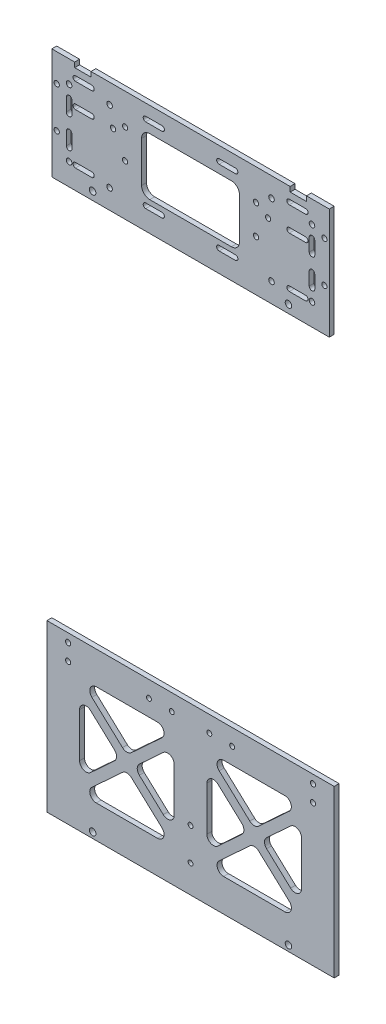
SolidWorks part; units mm, degrees
material "Thornel Mat VMA"
ref_plane "前视基准面" through (0, 0, 0) normal (0, 0, 1) x (1, 0, 0)
ref_plane "上视基准面" through (0, 0, 0) normal (0, 1, 0) x (1, 0, 0)
ref_plane "右视基准面" through (0, 0, 0) normal (1, 0, 0) x (0, 0, -1)
sketch "草图1" plane through (0, 0, 0) normal (0, 0, 1) x (1, 0, 0)
  line L0 (0, 211.445) -> (0, -244.9446) construction
  line L1 (-167.2368, 0) -> (136.1482, 0) construction
  line L3 (-88, -173.5) -> (88, -173.5)
  line L4 (-88, -173.5) -> (-88, 230)
  line L5 (-88, 230) -> (88, 230)
  line L6 (88, -173.5) -> (88, 230)
  line L7 (-88, -173.5) -> (88, 230) construction
  line L8 (-88, 230) -> (88, -173.5) construction
  circle A0 centre (-60, 170) radius 2
  circle A1 centre (60, 170) radius 2
  circle A2 centre (-60, -170) radius 2
  circle A3 centre (60, -170) radius 2
  point P14 (0, 28.25)
  dimension "D1" = 4
  dimension "D2" = 120
  dimension "D3" = 340
  dimension "D4" = 176
  dimension "D5" = 3.5
  dimension "D6" = 60
extrude "凸台-拉伸1" add sketch "草图1" along normal blind 3
sketch "草图3" plane through (0, 0, 0) normal (0, 0, -1) x (-1, 0, 0)
  line L0 (0, 280) -> (0, -209.7777) construction
  line L1 (-88, 230) -> (88, 230) construction
  line L2 (88, -173.5) -> (-88, -173.5) construction
  line L3 (-30, 218) -> (30, 218)
  line L4 (-30, 218) -> (-30, 183)
  line L5 (-30, 183) -> (30, 183)
  line L6 (30, 218) -> (30, 183)
  line L7 (-30, 218) -> (30, 183) construction
  line L8 (-30, 183) -> (30, 218) construction
  circle A0 centre (-40.1, 214) radius 1.6
  circle A1 centre (-40.1, 196) radius 1.6
  circle A2 centre (40.1, 214) radius 1.6
  circle A3 centre (40.1, 196) radius 1.6
  circle A4 centre (0, -136.5) radius 1.5
  circle A5 centre (0, -156.5) radius 1.5
  point P5 (0, 200.5)
  dimension "D4" = 80.2
  dimension "D5" = 18
  dimension "D6" = 3.2
  dimension "D7" = 16
  dimension "D8" = 3
  dimension "D9" = 20
  dimension "D10" = 17
  dimension "D1" = 60
  dimension "D2" = 12
  dimension "D3" = 35
extrude "切除-拉伸2" cut sketch "草图3" against normal through all
sketch "草图5" plane through (0, 0, 0) normal (0, 0, -1) x (-1, 0, 0)
  line L0 (88, -173.5) -> (-88, -173.5) construction
  line L1 (0, -173.5) -> (0, -19.6064) construction
  circle A0 centre (11.5, -81.85) radius 1.5
  circle A1 centre (25.5, -81.85) radius 1.5
  circle A2 centre (0, -136.5) radius 1.5 construction
  circle A3 centre (-25.5, -81.85) radius 1.5
  circle A4 centre (-11.5, -81.85) radius 1.5
  dimension "D1" = 3
  dimension "D2" = 14
  dimension "D3" = 11.5
  dimension "D4" = 91.65
extrude "切除-拉伸3" cut sketch "草图5" against normal through all
sketch "草图7" plane through (0, 0, 0) normal (0, 0, -1) x (-1, 0, 0)
  line L0 (0, 280) -> (0, -173.5) construction
  line L2 (88, -173.5) -> (-88, -173.5) construction
  line L3 (88, 230) -> (88, -173.5) construction
  line L4 (-68, 150) -> (68, 150) construction
  line L5 (-68, 150) -> (-68, -71.85) construction
  line L6 (-68, -71.85) -> (68, -71.85) construction
  line L7 (68, 150) -> (68, -71.85) construction
  line L8 (-68, 150) -> (68, -71.85) construction
  line L9 (-68, -71.85) -> (68, 150) construction
  line L11 (-68, -91.85) -> (-10, -91.85)
  line L12 (-68, -91.85) -> (-68, -153.5)
  line L13 (-68, -153.5) -> (-10, -153.5)
  line L14 (-10, -91.85) -> (-10, -153.5)
  line L15 (-68, -91.85) -> (-10, -153.5) construction
  line L16 (-68, -153.5) -> (-10, -91.85) construction
  line L17 (10, -91.85) -> (68, -91.85)
  line L18 (10, -91.85) -> (10, -153.5)
  line L19 (10, -153.5) -> (68, -153.5)
  line L20 (68, -91.85) -> (68, -153.5)
  line L21 (10, -91.85) -> (68, -153.5) construction
  line L22 (10, -153.5) -> (68, -91.85) construction
  circle A0 centre (25.5, -81.85) radius 1.5 construction
  circle A1 centre (60, 170) radius 2 construction
  circle A2 centre (25.5, -81.85) radius 1.5 construction
  point P6 (0, 39.075)
  point P17 (-39, -122.675)
  point P22 (39, -122.675)
  dimension "D1" = 10
  dimension "D2" = 20
  dimension "D3" = 20
  dimension "D4" = 20
  dimension "D5" = 20
  dimension "D6" = 10
  dimension "D7" = 20
extrude "切除-拉伸4" cut sketch "草图7" against normal through all
sketch "草图10" [suppressed] plane through (0, 0, 0) normal (0, 0, -1) x (-1, 0, 0)
  line L1 (80, 105) -> (-80, 105)
  line L2 (80, 105) -> (80, 160)
  line L3 (80, 160) -> (-80, 160)
  line L4 (-80, 105) -> (-80, 160)
  line L5 (80, 105) -> (-80, 160) construction
  line L6 (80, 160) -> (-80, 105) construction
  line L7 (0, 132.5) -> (0, 0) construction
  line L8 (-30, 185) -> (30, 185) construction
  point P0 (0, 132.5)
  dimension "D1" = 160
  dimension "D2" = 55
  dimension "D3" = 25
extrude "切除-拉伸6" [suppressed] cut sketch "草图10" against normal through all
sketch "草图11" plane through (0, 0, 0) normal (0, 0, -1) x (-1, 0, 0)
  line L0 (0, 230) -> (0, -173.5) construction
  line L1 (-88, 230) -> (88, 230) construction
  line L2 (88, -173.5) -> (-88, -173.5) construction
  line L3 (-204.8882, 0) -> (174.296, 0) construction
  line L4 (-88, -173.5) -> (-88, 230) construction
  line L5 (-88, 165) -> (88, 165)
  line L6 (-88, 165) -> (-88, -71.85)
  line L7 (-88, -71.85) -> (88, -71.85)
  line L8 (88, 165) -> (88, -71.85)
  line L9 (88, 230) -> (88, -173.5) construction
  circle A0 centre (25.5, -81.85) radius 1.5 construction
  circle A1 centre (60, 170) radius 2 construction
  circle A2 centre (-75, -77) radius 1.6
  circle A3 centre (-75, -87) radius 1.6
  circle A4 centre (75, -77) radius 1.6
  circle A5 centre (75, -87) radius 1.6
  circle A6 centre (-82, 216) radius 1.6
  circle A7 centre (-82, 191) radius 1.6
  circle A8 centre (82, 216) radius 1.6
  circle A9 centre (82, 191) radius 1.6
  dimension "D3" = 10
  dimension "D4" = 3.2
  dimension "D5" = 13
  dimension "D6" = 86.5
  dimension "D7" = 25
  dimension "D8" = 14
  dimension "D9" = 6
  dimension "D1" = 10
  dimension "D2" = 5
extrude "切除-拉伸7" cut sketch "草图11" against normal blind 10
sketch "草图12" plane through (0, 0, 0) normal (0, 0, -1) x (-1, 0, 0)
  line L0 (0, 264.3213) -> (0, 155.0913) construction
  line L1 (-88, 230) -> (88, 230) construction
  line L2 (-70.5, 226) -> (-60.5, 226)
  line L3 (-70.5, 226) -> (-70.5, 223)
  line L4 (-70.5, 223) -> (-60.5, 223)
  line L5 (-60.5, 226) -> (-60.5, 223)
  line L6 (-27.5, 226) -> (-17.5, 226)
  line L7 (-27.5, 226) -> (-27.5, 223)
  line L8 (-27.5, 223) -> (-17.5, 223)
  line L9 (-17.5, 226) -> (-17.5, 223)
  line L10 (70.5, 223) -> (60.5, 223)
  line L11 (60.5, 226) -> (60.5, 223)
  line L12 (70.5, 226) -> (60.5, 226)
  line L13 (70.5, 226) -> (70.5, 223)
  line L14 (27.5, 223) -> (17.5, 223)
  line L15 (17.5, 226) -> (17.5, 223)
  line L16 (27.5, 226) -> (17.5, 226)
  line L17 (27.5, 226) -> (27.5, 223)
  line L18 (-70.5, 211) -> (-70.5, 208)
  line L19 (-70.5, 211) -> (-60.5, 211)
  line L20 (-60.5, 211) -> (-60.5, 208)
  line L21 (-70.5, 208) -> (-60.5, 208)
  line L22 (-27.5, 211) -> (-27.5, 208)
  line L23 (-27.5, 211) -> (-17.5, 211)
  line L24 (-17.5, 211) -> (-17.5, 208)
  line L25 (-27.5, 208) -> (-17.5, 208)
  line L26 (27.5, 208) -> (17.5, 208)
  line L27 (17.5, 211) -> (17.5, 208)
  line L28 (27.5, 211) -> (17.5, 211)
  line L29 (27.5, 211) -> (27.5, 208)
  line L30 (70.5, 208) -> (60.5, 208)
  line L31 (60.5, 211) -> (60.5, 208)
  line L32 (70.5, 211) -> (60.5, 211)
  line L33 (70.5, 211) -> (70.5, 208)
  line L66 (-27.5, 180) -> (-27.5, 177)
  line L67 (-27.5, 180) -> (-17.5, 180)
  line L68 (-17.5, 180) -> (-17.5, 177)
  line L69 (-27.5, 177) -> (-17.5, 177)
  line L70 (27.5, 177) -> (17.5, 177)
  line L71 (17.5, 180) -> (17.5, 177)
  line L72 (27.5, 180) -> (17.5, 180)
  line L73 (27.5, 180) -> (27.5, 177)
  line L74 (70.5, 177) -> (60.5, 177)
  line L75 (60.5, 180) -> (60.5, 177)
  line L76 (70.5, 180) -> (60.5, 180)
  line L77 (70.5, 180) -> (70.5, 177)
  line L78 (-70.5, 180) -> (-70.5, 177)
  line L79 (-70.5, 180) -> (-60.5, 180)
  line L80 (-60.5, 180) -> (-60.5, 177)
  line L81 (-70.5, 177) -> (-60.5, 177)
  point P11 (-65.5, 226)
  point P12 (-22.5, 226)
  point P23 (-70.5, 209.5)
  point P24 (-70.5, 224.5)
  point P41 (-70.5, 178.5)
  dimension "D1" = 10
  dimension "D2" = 43
  dimension "D3" = 45
  dimension "D4" = 4
  dimension "D5" = 3
  dimension "D7" = 15
  dimension "D9" = 46
  dimension "D6" = 2
  dimension "D8" = 2
extrude "切除-拉伸8" cut sketch "草图12" against normal through all
sketch "草图13" plane through (0, 0, 0) normal (0, 0, -1) x (-1, 0, 0)
  line L0 (-60.5, 223) -> (-60.5, 226) construction
  line L1 (-70.5, 226) -> (-70.5, 223) construction
  line L2 (-27.5, 226) -> (-27.5, 223) construction
  line L3 (-17.5, 226) -> (-27.5, 226) construction
  line L4 (-17.5, 223) -> (-17.5, 226) construction
  line L5 (17.5, 226) -> (17.5, 223) construction
  line L6 (27.5, 223) -> (27.5, 226) construction
  line L7 (60.5, 226) -> (60.5, 223) construction
  line L8 (70.5, 223) -> (70.5, 226) construction
  circle A0 centre (-60.5, 224.5) radius 1.5
  circle A1 centre (-70.5, 224.5) radius 1.5
  circle A2 centre (-27.5, 224.5) radius 1.5
  circle A3 centre (-17.5, 224.5) radius 1.5
  circle A4 centre (17.5, 224.5) radius 1.5
  circle A5 centre (27.5, 224.5) radius 1.5
  circle A6 centre (60.5, 224.5) radius 1.5
  circle A7 centre (70.5, 224.5) radius 1.5
  circle A8 centre (-60.5, 209.5) radius 1.5
  circle A9 centre (-70.5, 209.5) radius 1.5
  circle A10 centre (-27.5, 209.5) radius 1.5
  circle A11 centre (-17.5, 209.5) radius 1.5
  circle A12 centre (17.5, 209.5) radius 1.5
  circle A13 centre (27.5, 209.5) radius 1.5
  circle A14 centre (60.5, 209.5) radius 1.5
  circle A15 centre (70.5, 209.5) radius 1.5
  circle A32 centre (-60.5, 178.5) radius 1.5
  circle A33 centre (-70.5, 178.5) radius 1.5
  circle A34 centre (-27.5, 178.5) radius 1.5
  circle A35 centre (-17.5, 178.5) radius 1.5
  circle A36 centre (17.5, 178.5) radius 1.5
  circle A37 centre (27.5, 178.5) radius 1.5
  circle A38 centre (60.5, 178.5) radius 1.5
  circle A39 centre (70.5, 178.5) radius 1.5
  dimension "D1" = 2
  dimension "D2" = 15
  dimension "D4" = 46
  dimension "D3" = 2
extrude "切除-拉伸9" cut sketch "草图13" against normal through all
fillet "圆角1" radius 5 4 edges at (-30, 183, 1.5) (30, 183, 1.5) (-30, 218, 1.5) (30, 218, 1.5)
sketch "草图14" plane through (0, 0, 0) normal (0, 0, -1) x (-1, 0, 0)
  line L0 (88, 165) -> (-88, 165) construction
  line L1 (-88, 230) -> (-85, 230)
  line L2 (-88, 230) -> (-88, 165)
  line L3 (-88, 165) -> (-85, 165)
  line L4 (-85, 230) -> (-85, 165)
  line L6 (88, 230) -> (85, 230)
  line L7 (88, 230) -> (88, 165)
  line L8 (88, 165) -> (85, 165)
  line L9 (85, 230) -> (85, 165)
  dimension "D1" = 3
extrude "切除-拉伸10" cut sketch "草图14" against normal through all
sketch "草图15" plane through (0, 0, 0) normal (0, 0, -1) x (-1, 0, 0)
  line L0 (0, 246.9086) -> (0, 165) construction
  line L1 (85, 165) -> (-85, 165) construction
  line L2 (-55, 200) -> (-21.4182, 200) construction
  line L3 (-56.5, 222.5) -> (-53.5, 222.5)
  line L4 (-56.5, 222.5) -> (-56.5, 212.5)
  line L5 (-56.5, 212.5) -> (-53.5, 212.5)
  line L6 (-53.5, 222.5) -> (-53.5, 212.5)
  line L7 (-56.5, 187.5) -> (-53.5, 187.5)
  line L8 (-56.5, 187.5) -> (-56.5, 177.5)
  line L9 (-56.5, 177.5) -> (-53.5, 177.5)
  line L10 (-53.5, 187.5) -> (-53.5, 177.5)
  line L11 (-55, 212.5) -> (-55, 187.5) construction
  line L12 (-85, 230) -> (85, 230) construction
  line L13 (56.5, 212.5) -> (53.5, 212.5)
  line L14 (53.5, 222.5) -> (53.5, 212.5)
  line L15 (56.5, 222.5) -> (53.5, 222.5)
  line L16 (56.5, 222.5) -> (56.5, 212.5)
  line L17 (56.5, 177.5) -> (53.5, 177.5)
  line L18 (53.5, 187.5) -> (53.5, 177.5)
  line L19 (56.5, 187.5) -> (53.5, 187.5)
  line L20 (56.5, 187.5) -> (56.5, 177.5)
  circle A0 centre (-55, 200) radius 1.5
  circle A1 centre (55, 200) radius 1.5
  point P17 (-53.5, 182.5)
  point P20 (-53.5, 217.5)
  dimension "D1" = 3
  dimension "D2" = 10
  dimension "D3" = 3
  dimension "D4" = 35
  dimension "D5" = 110
  dimension "D6" = 30
extrude "切除-拉伸11" cut sketch "草图15" against normal through all
sketch "草图16" plane through (0, 0, 3) normal (0, 0, 1) x (1, 0, 0)
  line L0 (-56.5, 222.5) -> (-53.5, 222.5) construction
  line L1 (-53.5, 212.5) -> (-56.5, 212.5) construction
  line L2 (-56.5, 187.5) -> (-53.5, 187.5) construction
  line L3 (-53.5, 177.5) -> (-56.5, 177.5) construction
  line L4 (53.5, 222.5) -> (56.5, 222.5) construction
  line L5 (56.5, 212.5) -> (53.5, 212.5) construction
  line L6 (53.5, 187.5) -> (56.5, 187.5) construction
  line L7 (56.5, 177.5) -> (53.5, 177.5) construction
  circle A0 centre (-55, 222.5) radius 1.5
  circle A1 centre (-55, 212.5) radius 1.5
  circle A2 centre (-55, 187.5) radius 1.5
  circle A3 centre (-55, 177.5) radius 1.5
  circle A4 centre (55, 222.5) radius 1.5
  circle A5 centre (55, 212.5) radius 1.5
  circle A6 centre (55, 187.5) radius 1.5
  circle A7 centre (55, 177.5) radius 1.5
extrude "切除-拉伸12" cut sketch "草图16" against normal through all
sketch "草图17" plane through (0, 0, 3) normal (0, 0, 1) x (1, 0, 0)
  line L0 (-68, -91.85) -> (-39, -118.594)
  line L1 (-10, -91.85) -> (-10, -153.5) construction
  line L2 (-10, -145.3381) -> (-10, -153.5)
  line L3 (-10, -153.5) -> (-39, -126.756)
  line L4 (-68, -153.5) -> (-68, -91.85) construction
  line L5 (-68, -100.0119) -> (-68, -91.85)
  line L6 (-10, -91.85) -> (-39, -118.594)
  line L7 (-68, -145.3381) -> (-68, -153.5)
  line L8 (-68, -153.5) -> (-39, -126.756)
  line L9 (-10, -100.0119) -> (-10, -91.85)
  line L10 (10, -91.85) -> (39, -118.594)
  line L11 (68, -91.85) -> (68, -153.5) construction
  line L12 (68, -145.3381) -> (68, -153.5)
  line L13 (68, -153.5) -> (39, -126.756)
  line L14 (10, -153.5) -> (10, -91.85) construction
  line L15 (10, -100.0119) -> (10, -91.85)
  line L16 (68, -91.85) -> (39, -118.594)
  line L17 (10, -145.3381) -> (10, -153.5)
  line L18 (10, -153.5) -> (39, -126.756)
  line L19 (68, -100.0119) -> (68, -91.85)
  line L20 (-34.5748, -122.675) -> (-10, -145.3381)
  line L21 (-43.4252, -122.675) -> (-68, -145.3381)
  line L22 (-34.5748, -122.675) -> (-10, -100.0119)
  line L23 (-43.4252, -122.675) -> (-68, -100.0119)
  line L24 (43.4252, -122.675) -> (68, -100.0119)
  line L25 (43.4252, -122.675) -> (68, -145.3381)
  line L26 (34.5748, -122.675) -> (10, -145.3381)
  line L27 (34.5748, -122.675) -> (10, -100.0119)
  dimension "D1" = 6
extrude "凸台-拉伸2" add sketch "草图17" against normal up to surface (3 mm away) up to face at (-76.6, -87, 0)
fillet "圆角2" radius 4 24 edges at (68, -145.3381, 1.5) (68, -153.5, 1.5) (10, -153.5, 1.5) (10, -145.3381, 1.5) (39, -126.756, 1.5) (34.5748, -122.675, 1.5) (43.4252, -122.675, 1.5) (68, -100.0119, 1.5) (39, -118.594, 1.5) (68, -91.85, 1.5) (10, -91.85, 1.5) (10, -100.0119, 1.5) (-10, -145.3381, 1.5) (-10, -153.5, 1.5) (-68, -153.5, 1.5) (-68, -145.3381, 1.5) (-43.4252, -122.675, 1.5) (-34.5748, -122.675, 1.5) (-39, -118.594, 1.5) (-68, -100.0119, 1.5) (-39, -126.756, 1.5) (-10, -100.0119, 1.5) (-10, -91.85, 1.5) (-68, -91.85, 1.5)
sketch "草图18" plane through (0, 0, 0) normal (0, 0, -1) x (-1, 0, 0)
  line L0 (-72, 209.5) -> (59, 209.5) construction
  line L1 (0, 230) -> (0, 193.925) construction
  line L2 (-85, 230) -> (85, 230) construction
  arc A0 (-70.5, 211) -> (-70.5, 208) centre (-70.5, 209.5) ccw construction
  arc A1 (60.5, 211) -> (60.5, 208) centre (60.5, 209.5) ccw construction
  circle A2 centre (-47.5, 209.5) radius 1.6
  circle A3 centre (47.5, 209.5) radius 1.6
  dimension "D1" = 3.2
  dimension "D2" = 95
extrude "切除-拉伸13" cut sketch "草图18" against normal through all
sketch "草图19" plane through (0, 0, 0) normal (0, 0, -1) x (-1, 0, 0)
  line L0 (85, 230) -> (85, 165) construction
  line L1 (-85, 230) -> (-71, 230)
  line L2 (-85, 230) -> (-85, 233)
  line L3 (-85, 233) -> (-71, 233)
  line L4 (85, 230) -> (85, 233)
  line L5 (-71, 233) -> (-71, 230)
  line L6 (-61, 233) -> (-61, 230)
  line L7 (0, 183) -> (0, 237.3182) construction
  line L8 (-25, 183) -> (25, 183) construction
  line L9 (61, 233) -> (61, 230)
  line L10 (71, 233) -> (71, 230)
  line L11 (-85, 165) -> (-85, 230) construction
  line L12 (-61, 233) -> (61, 233)
  line L13 (71, 233) -> (85, 233)
  line L14 (-61, 230) -> (61, 230)
  line L15 (71, 230) -> (85, 230)
  dimension "D1" = 3
  dimension "D2" = 14
  dimension "D3" = 10
extrude "凸台-拉伸3" add sketch "草图19" against normal up to surface (3 mm away) up to face at (45.9, 209.5, 3)
sketch "草图20" plane through (0, 0, 3) normal (0, 0, 1) x (1, 0, 0)
  line L0 (74.4, 186) -> (74.4, 194) construction
  line L1 (72.7, 186) -> (72.7, 194)
  line L2 (76.1, 186) -> (76.1, 194)
  line L3 (74.4, 204) -> (74.4, 212) construction
  line L4 (72.7, 204) -> (72.7, 212)
  line L5 (76.1, 204) -> (76.1, 212)
  line L6 (85, 165) -> (85, 233) construction
  line L7 (85, 233) -> (71, 233) construction
  line L8 (-85, 165) -> (85, 165) construction
  line L9 (0, 165) -> (0, 264.3893) construction
  line L10 (-74.4, 204) -> (-74.4, 212) construction
  line L11 (-72.7, 204) -> (-72.7, 212)
  line L12 (-76.1, 204) -> (-76.1, 212)
  line L13 (-74.4, 186) -> (-74.4, 194) construction
  line L14 (-72.7, 186) -> (-72.7, 194)
  line L15 (-76.1, 186) -> (-76.1, 194)
  circle A0 centre (74.4, 219.5) radius 1.7
  circle A1 centre (74.4, 178.5) radius 1.7
  arc A2 (72.7, 186) -> (76.1, 186) centre (74.4, 186) ccw
  arc A3 (76.1, 194) -> (72.7, 194) centre (74.4, 194) ccw
  arc A4 (72.7, 204) -> (76.1, 204) centre (74.4, 204) ccw
  arc A5 (76.1, 212) -> (72.7, 212) centre (74.4, 212) ccw
  circle A6 centre (-74.4, 178.5) radius 1.7
  circle A7 centre (-74.4, 219.5) radius 1.7
  arc A8 (-72.7, 204) -> (-76.1, 204) centre (-74.4, 204) cw
  arc A9 (-76.1, 212) -> (-72.7, 212) centre (-74.4, 212) cw
  arc A10 (-72.7, 186) -> (-76.1, 186) centre (-74.4, 186) cw
  arc A11 (-76.1, 194) -> (-72.7, 194) centre (-74.4, 194) cw
  point P6 (74.4, 190)
  point P11 (74.4, 208)
  point P33 (-74.4, 208)
  point P40 (-74.4, 190)
  dimension "D1" = 10.6
  dimension "D2" = 13.5
  dimension "D3" = 3.4
  dimension "D4" = 10.6
  dimension "D5" = 13.5
  dimension "D6" = 3.4
  dimension "D8" = 1.7
  dimension "D9" = 7.5
  dimension "D10" = 7.5
  dimension "D11" = 1.7
  dimension "D7" = 8
  dimension "D12" = 8
extrude "切除-拉伸14" cut sketch "草图20" against normal blind 10
sketch "草图21" plane through (0, 0, 3) normal (0, 0, 1) x (1, 0, 0)
  line L0 (-53.5, 187.5) -> (-53.5, 177.5) construction
  line L1 (-56.5, 177.5) -> (-56.5, 187.5) construction
  line L2 (-53.5, 222.5) -> (-53.5, 212.5) construction
  line L3 (-56.5, 212.5) -> (-56.5, 222.5) construction
  line L4 (53.5, 177.5) -> (53.5, 187.5) construction
  line L5 (56.5, 187.5) -> (56.5, 177.5) construction
  line L6 (56.5, 222.5) -> (56.5, 212.5) construction
  line L7 (53.5, 212.5) -> (53.5, 222.5) construction
  line L8 (-53.5, 187.5) -> (-53.5, 177.5)
  line L9 (-56.5, 177.5) -> (-56.5, 187.5)
  line L10 (-53.5, 222.5) -> (-53.5, 212.5)
  line L11 (-56.5, 212.5) -> (-56.5, 222.5)
  line L12 (53.5, 177.5) -> (53.5, 187.5)
  line L13 (56.5, 187.5) -> (56.5, 177.5)
  line L14 (56.5, 222.5) -> (56.5, 212.5)
  line L15 (53.5, 212.5) -> (53.5, 222.5)
  circle A0 centre (-55, 200) radius 1.5 construction
  arc A1 (-56.5, 177.5) -> (-53.5, 177.5) centre (-55, 177.5) ccw construction
  arc A2 (-53.5, 187.5) -> (-56.5, 187.5) centre (-55, 187.5) ccw construction
  arc A3 (-53.5, 222.5) -> (-56.5, 222.5) centre (-55, 222.5) ccw construction
  arc A4 (-56.5, 212.5) -> (-53.5, 212.5) centre (-55, 212.5) ccw construction
  arc A5 (53.5, 177.5) -> (56.5, 177.5) centre (55, 177.5) ccw construction
  arc A6 (56.5, 187.5) -> (53.5, 187.5) centre (55, 187.5) ccw construction
  circle A7 centre (55, 200) radius 1.5 construction
  arc A8 (56.5, 222.5) -> (53.5, 222.5) centre (55, 222.5) ccw construction
  arc A9 (53.5, 212.5) -> (56.5, 212.5) centre (55, 212.5) ccw construction
  circle A10 centre (-55, 200) radius 1.5
  arc A11 (-56.5, 177.5) -> (-53.5, 177.5) centre (-55, 177.5) ccw
  arc A12 (-53.5, 187.5) -> (-56.5, 187.5) centre (-55, 187.5) ccw
  arc A13 (-53.5, 222.5) -> (-56.5, 222.5) centre (-55, 222.5) ccw
  arc A14 (-56.5, 212.5) -> (-53.5, 212.5) centre (-55, 212.5) ccw
  arc A15 (53.5, 177.5) -> (56.5, 177.5) centre (55, 177.5) ccw
  arc A16 (56.5, 187.5) -> (53.5, 187.5) centre (55, 187.5) ccw
  circle A17 centre (55, 200) radius 1.5
  arc A18 (56.5, 222.5) -> (53.5, 222.5) centre (55, 222.5) ccw
  arc A19 (53.5, 212.5) -> (56.5, 212.5) centre (55, 212.5) ccw
extrude "凸台-拉伸4" add sketch "草图21" against normal blind 3
sketch "草图22" plane through (0, 0, 3) normal (0, 0, 1) x (1, 0, 0)
  line L0 (85, 165) -> (85, 233) construction
  line L1 (61, 233) -> (-61, 233) construction
  line L2 (0, 165) -> (0, 242.5506) construction
  line L3 (-85, 165) -> (85, 165) construction
  circle A0 centre (49.6, 221) radius 1.7
  circle A1 centre (49.6, 177) radius 1.7
  circle A2 centre (-49.6, 177) radius 1.7
  circle A3 centre (-49.6, 221) radius 1.7
  dimension "D1" = 35.4
  dimension "D2" = 3.4
  dimension "D3" = 12
  dimension "D4" = 3.4
  dimension "D5" = 35.4
  dimension "D6" = 44
extrude "切除-拉伸15" cut sketch "草图22" against normal blind 3
